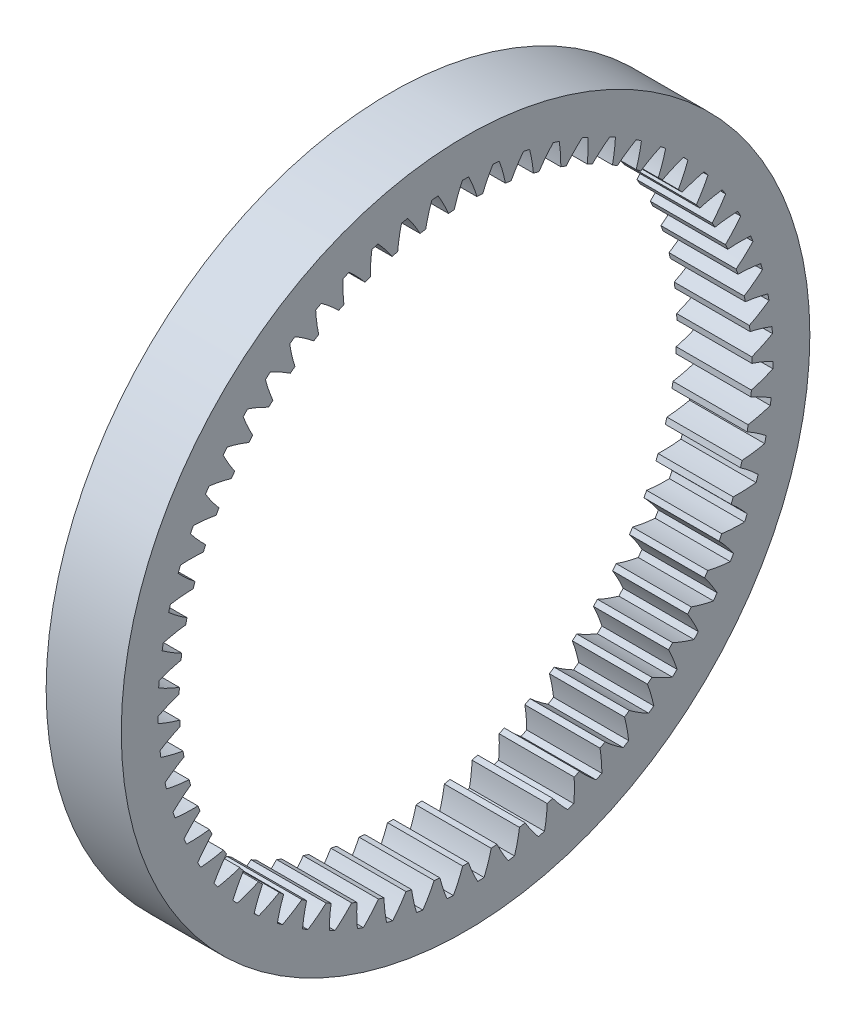
SolidWorks part; units mm, degrees
ref_plane "Plane1" through (0, 0, 0) normal (0, 0, 1) x (1, 0, 0)
ref_plane "Plane2" through (0, 0, 0) normal (0, 1, 0) x (1, 0, 0)
ref_plane "Plane3" through (0, 0, 0) normal (1, 0, 0) x (0, 0, -1)
sketch "HoldingSke" plane through (0, 0, 0) normal (0, 1, 0) x (1, 0, 0)
  line L0 (0, 0) -> (0.3027, -0.594)
  line L1 (-15, 0) -> (100, 0) construction
  line L2 (0, 0) -> (-2.1039, 2.3779)
  line L3 (0, 0) -> (-11.863, 4.5341)
  line L4 (0, 0) -> (3.9207, 7.6947)
  line L5 (0, 0) -> (-23.7986, -8.8762)
  line L6 (0, 0) -> (-10.5278, -7.1032)
  line L7 (-2.1039, 2.3779) -> (3.3635, 27.1825)
  line L8 (-76.2, 3.8779) -> (-54.61, 3.8779)
  line L9 (-71.009, 38.7566) -> (-53.1078, 45.2721)
  line L10 (-76.2, 71.12) -> (104.1128, 71.12)
  line L11 (0, 0) -> (-12, 0)
  line L12 (-76.2, 101.6) -> (-76.147, 101.6)
  line L13 (24.9733, 27.94) -> (52.9518, 28.4284)
  line L14 (24.9733, 27.94) -> (24.9743, 27.94)
  line L15 (24.9733, 27.94) -> (100.4006, 29.5858)
  circle A0 centre (0, 0) radius 55
  circle A1 centre (0, 0) radius 12.7
  circle A2 centre (0, 0) radius 12.7
  dimension "MHD" = 25.4
  dimension "Hub_dia" = 25.4
  dimension "Diameter" = 110
  dimension "Num_teeth" = 63
  dimension "Pitch" = 0.6667
  dimension "Overall_len" = 25.4
  dimension "Show_teeth" = 63
  dimension "Thickness" = 12.7
  dimension "OAL" = 25.4001
  dimension "T_dim" = 21.59
  dimension "Ap" = 20
  dimension "H" = 19.05
  dimension "Pitch_radius" = 180.3128
  dimension "Width" = 12
  dimension "Backlash" = 0.053
  dimension "Addendum_fac" = 1
  dimension "Dedendum_fac" = 1.25
  dimension "Clearance_fac" = 0.25
  dimension "Dedendum_add" = 0.001
  dimension "Module" = 1.5
sketch "BasProSke" plane through (0, 0, 0) normal (0, 1, 0) x (1, 0, 0)
  line L0 (-10, 0) -> (60, 0) construction
  line L1 (0, 45.75) -> (0, 55)
  line L2 (0, 45.75) -> (12, 45.75)
  line L3 (12, 45.75) -> (12, 55)
  line L4 (12, 55) -> (0, 55)
  dimension "Diameter" = 110
  dimension "Thickness" = 12
  dimension "Inside_diameter" = 91.5
revolve "Base-Revolve" add sketch "BasProSke" angle 360 about L0
sketch "TooCutSke" plane through (0, 0, 0) normal (1, 0, 0) x (0, 0, -1)
  line L3 (1.3105, 47.2318) -> (1.3105, 53.6633) construction
  line L4 (0, 0) -> (0, 59.563) construction
  line L5 (0, 0) -> (-3.4058, 68.2426) construction
  line L6 (-20.8232, 38.9709) -> (35.8039, 41.7971) construction
  circle A0 centre (0, 0) radius 47.25 construction
  circle A1 centre (0, 0) radius 49.126 construction
  circle A2 centre (0, 0) radius 39.9604 construction
  circle A3 centre (0, 0) radius 45.7246 construction
  arc A4 (1.8268, 45.6881) -> (0.5092, 49.1234) centre (-20.8232, 38.9709) ccw
  arc A5 (1.8268, 45.6881) -> (-1.8268, 45.6881) centre (0, 0) ccw
  arc A6 (0.5092, 49.1234) -> (-0.5092, 49.1234) centre (0, 0) ccw
  arc A7 (-0.5092, 49.1234) -> (-1.8268, 45.6881) centre (20.8232, 38.9709) ccw
  dimension "Pitch_dia" = 94.5
  dimension "Base_dia" = 79.9209
  dimension "Root_dia" = 98.252
  dimension "Overcut_dia" = 91.4492
  dimension "Flank_rad" = 23.625
  dimension "Half_ang" = 2.857
  dimension "Half_CT" = 1.3105
extrude "ToothCut" cut sketch "TooCutSke" along normal through all
fillet "Breaks" [suppressed] radius 0.15
fillet "RootFillets" [suppressed] radius 0.376
pattern_circular "TeethCuts" count 63 every 5.714 about axis through (-10, 0, 0) along (1, 0, 0) of "RootFillets", "Breaks", "ToothCut"
equation "' \"Module@HoldingSke\" = 6.35"
equation "' \"Num_teeth@HoldingSke\" = 24"
equation "' \"Ap@HoldingSke\" =  14.5"
equation "' \"Ap@HoldingSke\" = 14.5"
equation "' \"Width@HoldingSke\" = 12"
equation "' \"Diameter@HoldingSke\" = 8 * 25.4"
equation "' \"Show_teeth@HoldingSke\" = 100"
equation "' \"Backlash@HoldingSke\" = 0.009 * 25.4"
equation "' \"Addendum_fac@HoldingSke\" = 1.0"
equation "' \"Dedendum_fac@HoldingSke\" = 1.25"
equation "' \"Dedendum_add@HoldingSke\" = 0.00005 * 25.4"
equation "' \"Clearance_fac@HoldingSke\" = 0.25"
equation "\"Pitch@HoldingSke\" = 1 / \"Module@HoldingSke\" "
equation "\"Overcut_dia@TooCutSke\" = (\"Num_teeth@HoldingSke\" - 2 * \"Addendum_fac@HoldingSke\") / \"Pitch@HoldingSke\" - 0.002 * 25.4"
equation "\"Pitch_dia@TooCutSke\" = \"Num_teeth@HoldingSke\" / \"Pitch@HoldingSke\""
equation "\"Base_dia@TooCutSke\" = \"Num_teeth@HoldingSke\" / \"Pitch@HoldingSke\" * cos((\"Ap@HoldingSke\"  * 3.14159265 / 180)) * 0.90"
equation "\"Root_dia@TooCutSke\" = \"Num_teeth@HoldingSke\"  / \"Pitch@HoldingSke\" + 2 *  \"Dedendum_fac@HoldingSke\"/ \"Pitch@HoldingSke\" + \"Dedendum_add@HoldingSke\" * 2"
equation "\"Half_ang@TooCutSke\" = 180 / \"Num_teeth@HoldingSke\""
equation "\"Half_CT@TooCutSke\" = \"Num_teeth@HoldingSke\" / \"Pitch@HoldingSke\" * sin((3.14159265 / 2 / \"Num_teeth@HoldingSke\")) / 2 + 10 * \"Backlash@HoldingSke\" / 4"
equation "\"Flank_rad@TooCutSke\" = \"Num_teeth@HoldingSke\" / \"Pitch@HoldingSke\" / 4"
equation "\"Radius@RootFillets\"= \"Clearance_fac@HoldingSke\" / \"Pitch@HoldingSke\" + \"Dedendum_add@HoldingSke\""
equation "\"Break_rad@Breaks\" = 0.02 / \"Pitch@HoldingSke\" * 5"
equation "\"Num_teeth@TeethCuts\" = int( \"Show_teeth@HoldingSke\" ) + 1"
equation "\"Num_teeth@TeethCuts\" = ((sgn( \"Num_teeth@TeethCuts\" - \"Num_teeth@HoldingSke\" )-1)*( \"Num_teeth@TeethCuts\" - \"Num_teeth@HoldingSke\" ))/-2+ \"Num_teeth@HoldingSke\""
equation "\"Num_teeth@TeethCuts\" = ((sgn( \"Num_teeth@TeethCuts\" - 2.0)+1)*( \"Num_teeth@TeethCuts\" - 2.0))/2 +2.0"
equation "\"Angle@TeethCuts\" = 360.0 / \"Num_teeth@HoldingSke\""
equation "\"Diameter@BasProSke\" = \"Num_teeth@HoldingSke\"  / \"Pitch@HoldingSke\" + 2 *  \"Dedendum_fac@HoldingSke\"/ \"Pitch@HoldingSke\" + \"Dedendum_add@HoldingSke\" * 2 + 0.002 * 25.4"
equation "\"Diameter@BasProSke\" = ((sgn( \"Diameter@BasProSke\"  - \"Diameter@HoldingSke\" )+1)*( \"Diameter@BasProSke\"  - \"Diameter@HoldingSke\" ))/2 + \"Diameter@HoldingSke\""
equation "\"Inside_diameter@BasProSke\" =  (\"Num_teeth@HoldingSke\" - 2 * \"Addendum_fac@HoldingSke\") / \"Pitch@HoldingSke\" "
equation "\"Thickness@BasProSke\"  = \"Width@HoldingSke\""
